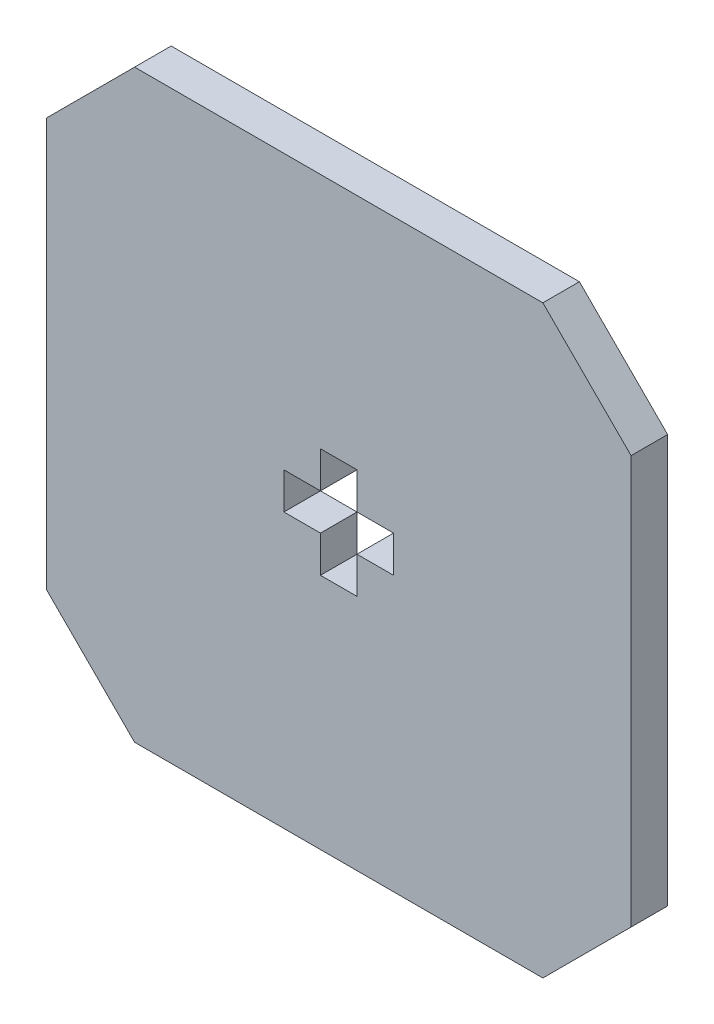
SolidWorks part; units mm, degrees
ref_plane "Front Plane" through (0, 0, 0) normal (0, 0, 1) x (1, 0, 0)
ref_plane "Top Plane" through (0, 0, 0) normal (0, 1, 0) x (1, 0, 0)
ref_plane "Right Plane" through (0, 0, 0) normal (1, 0, 0) x (0, 0, -1)
sketch "Sketch1" plane through (0, 0, 0) normal (0, 0, 1) x (1, 0, 0)
  line L1085 (364.5, 277.5) -> (364.5, 274.5)
  line L1086 (364.5, 274.5) -> (367.5, 274.5)
  line L1087 (367.5, 274.5) -> (367.5, 271.5)
  line L1088 (367.5, 271.5) -> (364.5, 271.5)
  line L1089 (364.5, 271.5) -> (364.5, 268.5)
  line L1090 (364.5, 268.5) -> (361.5, 268.5)
  line L1091 (361.5, 268.5) -> (361.5, 271.5)
  line L1092 (361.5, 271.5) -> (358.5, 271.5)
  line L1093 (358.5, 271.5) -> (358.5, 274.5)
  line L1094 (358.5, 274.5) -> (361.5, 274.5)
  line L1095 (361.5, 274.5) -> (361.5, 277.5)
  line L1096 (361.5, 277.5) -> (364.5, 277.5)
  line L1097 (346.2426, 249) -> (339, 256.2426)
  line L1098 (339, 256.2426) -> (339, 289.7574)
  line L1099 (339, 289.7574) -> (346.2426, 297)
  line L1100 (346.2426, 297) -> (379.7574, 297)
  line L1101 (379.7574, 297) -> (387, 289.7574)
  line L1102 (387, 289.7574) -> (387, 256.2426)
  line L1103 (387, 256.2426) -> (379.7574, 249)
  line L1104 (379.7574, 249) -> (346.2426, 249)
extrude "Boss-Extrude1" add sketch "Sketch1" along normal blind 3
